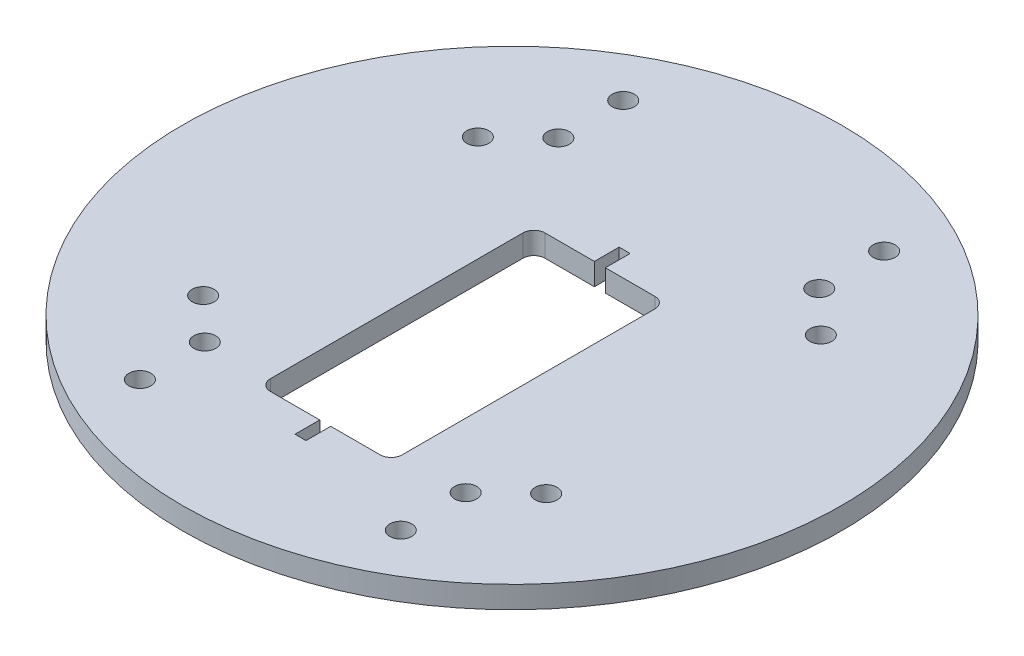
SolidWorks part; units mm, degrees
ref_plane "Front Plane" through (0, 0, 0) normal (0, 0, 1) x (1, 0, 0)
ref_plane "Top Plane" through (0, 0, 0) normal (0, 1, 0) x (1, 0, 0)
ref_plane "Right Plane" through (0, 0, 0) normal (1, 0, 0) x (0, 0, -1)
sketch "Sketch1" plane through (0, 0, 0) normal (0, 1, 0) x (1, 0, 0)
  line L1 (-11.8743, 22) -> (11.8743, 22) construction
  line L2 (-11.8743, 22) -> (-11.8743, -22) construction
  line L3 (-11.8743, -22) -> (11.8743, -22) construction
  line L4 (11.8743, 22) -> (11.8743, -22) construction
  line L5 (-11.8743, 22) -> (11.8743, -22) construction
  line L6 (-11.8743, -22) -> (11.8743, 22) construction
  line L7 (15.6125, -12.5) -> (-15.6125, -12.5) construction
  line L8 (15.6125, -12.5) -> (15.6125, 12.5) construction
  line L9 (15.6125, 12.5) -> (-15.6125, 12.5) construction
  line L10 (-15.6125, -12.5) -> (-15.6125, 12.5) construction
  line L11 (15.6125, -12.5) -> (-15.6125, 12.5) construction
  line L12 (15.6125, 12.5) -> (-15.6125, -12.5) construction
  circle A0 centre (0, 0) radius 30
  circle A1 centre (-11.8743, 22) radius 1
  circle A2 centre (11.8743, 22) radius 1
  circle A3 centre (11.8743, -22) radius 1
  circle A4 centre (-11.8743, -22) radius 1
  circle A5 centre (0, 0) radius 20 construction
  circle A6 centre (-11.8743, 16.0935) radius 1
  circle A7 centre (11.8743, 16.0935) radius 1
  circle A8 centre (11.8743, -16.0935) radius 1
  circle A9 centre (-11.8743, -16.0935) radius 1
  circle A10 centre (-15.6125, 12.5) radius 1
  circle A11 centre (15.6125, 12.5) radius 1
  circle A12 centre (15.6125, -12.5) radius 1
  circle A13 centre (-15.6125, -12.5) radius 1
  dimension "D1" = 60
  dimension "D4" = 2
  dimension "D5" = 40
  dimension "D6" = 2
  dimension "D8" = 2
  dimension "D2" = 50
  dimension "D3" = 44
  dimension "D7" = 25
extrude "Boss-Extrude1" add sketch "Sketch1" along normal blind 2
sketch "Sketch2" plane through (0, 2, 0) normal (0, 1, 0) x (1, 0, 0)
  line L0 (-24.5177, 0) -> (24.8379, 0) construction
  line L1 (0, 25.0963) -> (0, 8) construction
  line L2 (-4.9303, -4.5) -> (4.2882, -4.5) construction
  line L3 (-5, 8) -> (-0.5, 8)
  line L4 (-6, 7) -> (-6, -16)
  line L5 (-5, -17) -> (-0.5, -17)
  line L6 (6, 7) -> (6, -16)
  line L7 (-6, 8) -> (6, -17) construction
  line L8 (-6, -17) -> (6, 8) construction
  line L9 (0, 5.75) -> (0, -14.75) construction
  line L10 (-0.5, 10.25) -> (0.5, 10.25)
  line L11 (-0.5, 10.25) -> (-0.5, 8)
  line L13 (0.5, 10.25) -> (0.5, 8)
  line L14 (-0.5, 10.25) -> (0, 8) construction
  line L15 (0, 8) -> (0.5, 10.25) construction
  line L17 (-0.5, -17) -> (-0.5, -19.25)
  line L18 (-0.5, -19.25) -> (0.5, -19.25)
  line L19 (0.5, -17) -> (0.5, -19.25)
  line L20 (0, -17) -> (0.5, -19.25) construction
  line L21 (-0.5, -19.25) -> (0, -17) construction
  line L22 (0, -17) -> (0, -23.7628) construction
  line L23 (0.5, 8) -> (5, 8)
  line L24 (0.5, -17) -> (5, -17)
  arc A0 (5, -17) -> (6, -16) centre (5, -16) ccw
  arc A1 (-6, -16) -> (-5, -17) centre (-5, -16) ccw
  arc A2 (5, 8) -> (6, 7) centre (5, 7) cw
  arc A3 (-5, 8) -> (-6, 7) centre (-5, 7) ccw
  point P5 (0, -4.5)
  point P10 (0, 8)
  point P17 (0, -17)
  point P22 (0, -19.25)
  dimension "D4" = 1
  dimension "D1" = 4.5
  dimension "D2" = 25
  dimension "D3" = 12
  dimension "D5" = 1
  dimension "D6" = 0.5
extrude "Cut-Extrude1" cut sketch "Sketch2" against normal through all both and the other way through all
